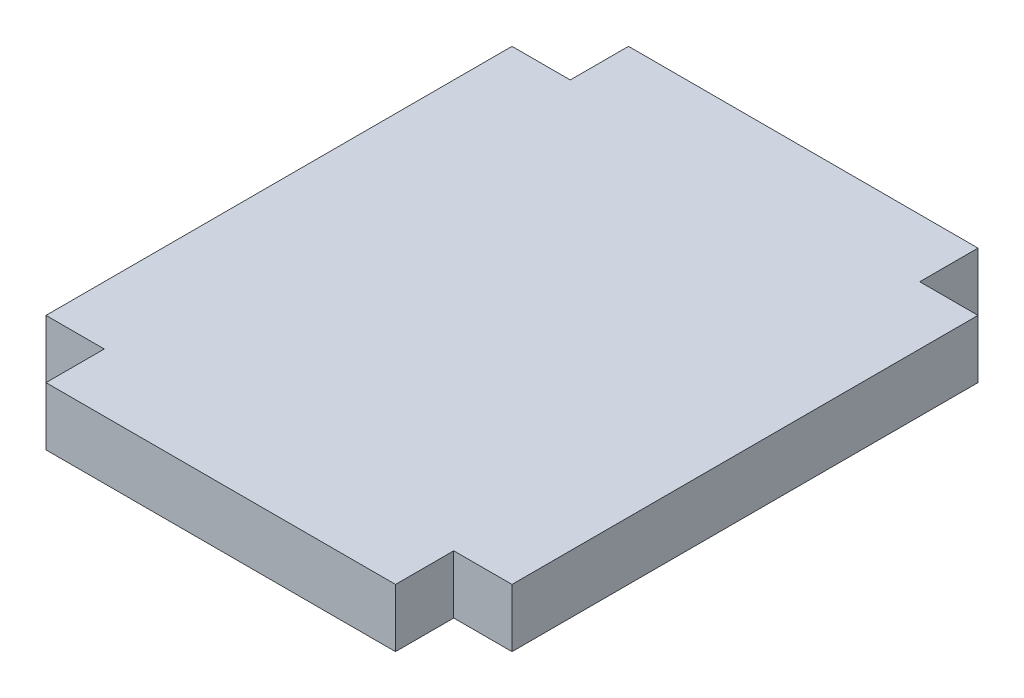
SolidWorks part; units mm, degrees
ref_plane "Alzado" through (0, 0, 0) normal (0, 0, 1) x (1, 0, 0)
ref_plane "Planta" through (0, 0, 0) normal (0, 1, 0) x (1, 0, 0)
ref_plane "Vista lateral" through (0, 0, 0) normal (1, 0, 0) x (0, 0, -1)
sketch "Croquis1" plane through (0, 0, 0) normal (0, 1, 0) x (1, 0, 0)
  line L0 (0, 0) -> (18, 0)
  line L1 (18, 0) -> (18, 3)
  line L2 (21, 3) -> (18, 3)
  line L3 (21, 3) -> (21, 27)
  line L4 (21, 27) -> (18, 27)
  line L5 (18, 27) -> (18, 30)
  line L6 (18, 30) -> (0, 30)
  line L8 (0, 27) -> (0, 30)
  line L9 (-3, 27) -> (0, 27)
  line L10 (-3, 3) -> (-3, 27)
  line L11 (0, 0) -> (0, 3)
  line L12 (18, 3) -> (18.0793, 3.0175)
  line L13 (0, 3) -> (-3, 3)
  point P13 (9, 30)
  dimension "D1" = 3
  dimension "D2" = 18
  dimension "D4" = 24
  dimension "D5" = 3
extrude "Saliente-Extruir1" add sketch "Croquis1" along normal blind 3
